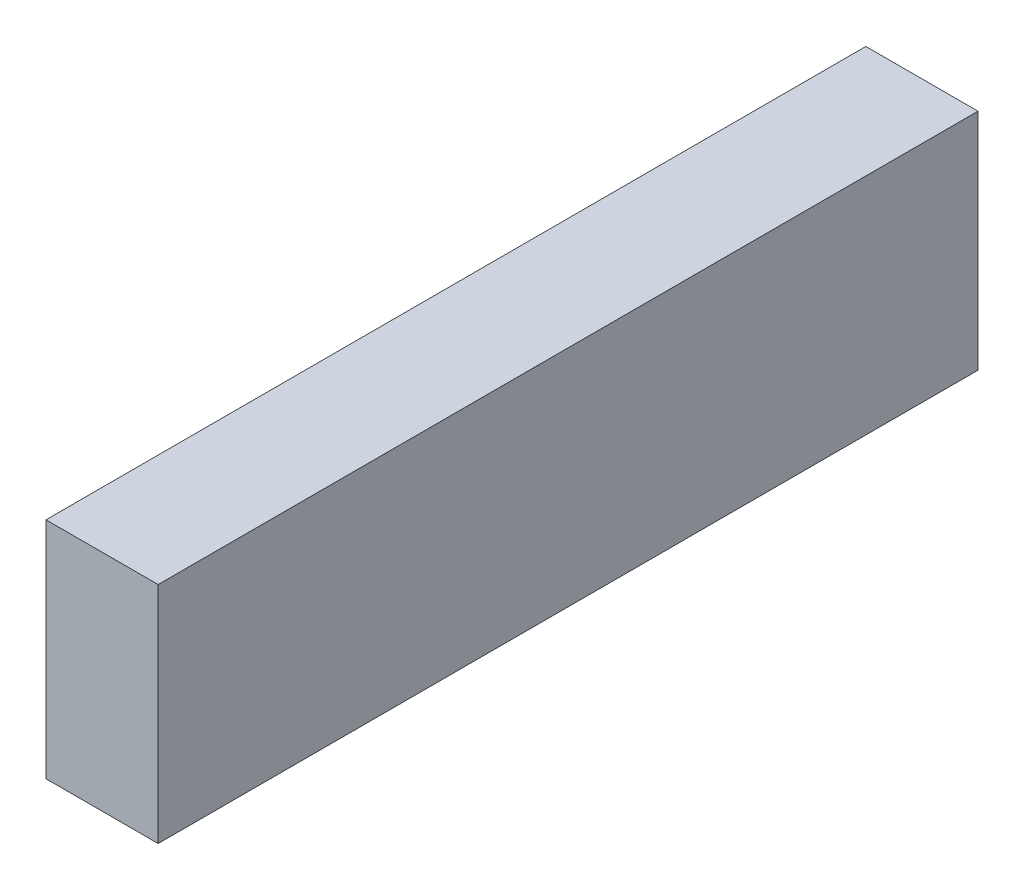
SolidWorks part; units mm, degrees
ref_plane "Front Plane" through (0, 0, 0) normal (0, 0, 1) x (1, 0, 0)
ref_plane "Top Plane" through (0, 0, 0) normal (0, 1, 0) x (1, 0, 0)
ref_plane "Right Plane" through (0, 0, 0) normal (1, 0, 0) x (0, 0, -1)
sketch "Sketch1" plane through (0, 0, 0) normal (1, 0, 0) x (0, 0, -1)
  line L1 (0, 0) -> (73.1, 0)
  line L2 (0, 0) -> (0, 20)
  line L3 (0, 20) -> (73.1, 20)
  line L4 (73.1, 0) -> (73.1, 20)
extrude "Boss-Extrude1" add sketch "Sketch1" along normal blind 10
